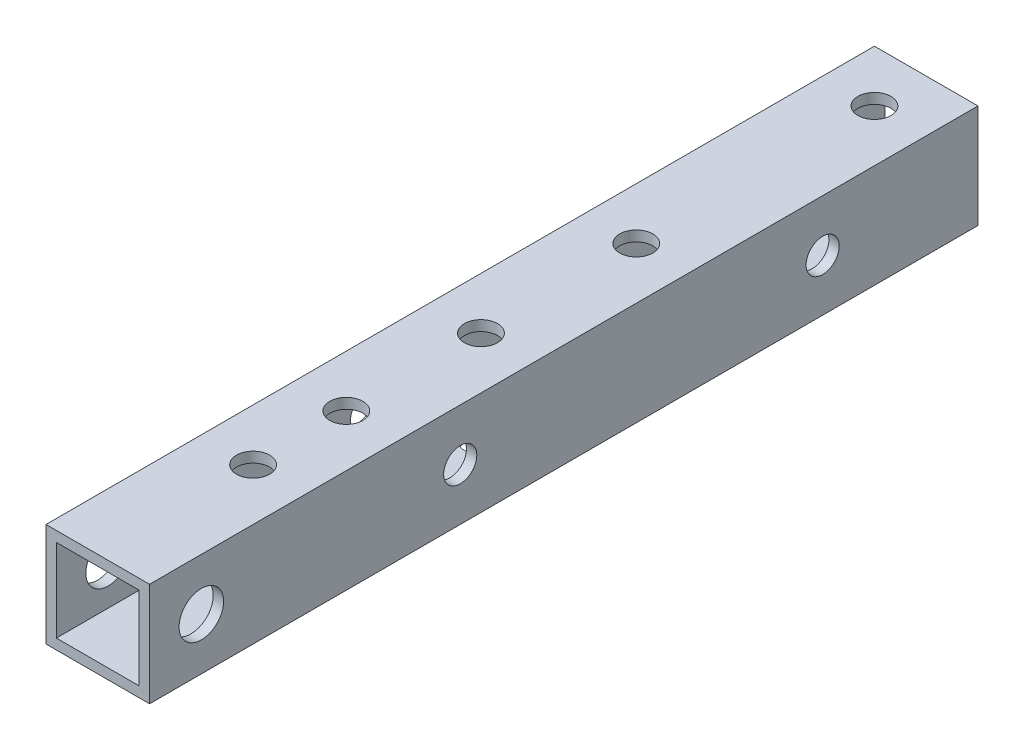
SolidWorks part; units mm, degrees
material "1060 合金"
ref_plane "正面" through (0, 0, 0) normal (0, 0, 1) x (1, 0, 0)
ref_plane "平面" through (0, 0, 0) normal (0, 1, 0) x (1, 0, 0)
ref_plane "右側面" through (0, 0, 0) normal (1, 0, 0) x (0, 0, -1)
sketch "ｽｹｯﾁ1" plane through (0, 0, 0) normal (0, 0, 1) x (1, 0, 0)
  line L1 (5, 5) -> (-5, 5)
  line L2 (5, 5) -> (5, -5)
  line L3 (5, -5) -> (-5, -5)
  line L4 (-5, 5) -> (-5, -5)
  line L5 (5, 5) -> (-5, -5) construction
  line L6 (5, -5) -> (-5, 5) construction
  point P0 (0, 0)
  dimension "D1" = 10
extrude "押し出し-薄板1" add sketch "ｽｹｯﾁ1" along normal blind 80 thin thin type one direction reverse wall 1
sketch "ｽｹｯﾁ2" plane through (0, 5, 0) normal (0, 1, 0) x (1, 0, 0)
  line L0 (0, 0) -> (0, -80) construction
  line L1 (5, 0) -> (-5, 0) construction
  line L2 (5, -80) -> (-5, -80) construction
  circle A0 centre (0, -5) radius 1.6
  dimension "D1" = 3.2
  dimension "D2" = 5
extrude "ｶｯﾄ - 押し出し1" cut sketch "ｽｹｯﾁ2" against normal through all
sketch "ｽｹｯﾁ3" plane through (5, 0, 0) normal (1, 0, 0) x (0, 0, -1)
  line L0 (0, 0) -> (-80, 0) construction
  line L1 (-80, -5) -> (-80, 5) construction
  line L2 (0, -5) -> (0, 5) construction
  circle A0 centre (-15, 0) radius 1.6
  dimension "D1" = 15
  dimension "D2" = 3.2
extrude "ｶｯﾄ - 押し出し2" cut sketch "ｽｹｯﾁ3" against normal through all
sketch "ｽｹｯﾁ4" plane through (0, -5, 0) normal (0, -1, 0) x (1, 0, 0)
  line L0 (0, 80) -> (0, 0) construction
  line L1 (-5, 80) -> (5, 80) construction
  line L2 (-5, 0) -> (5, 0) construction
  circle A0 centre (0, 65) radius 1.6
  circle A1 centre (0, 56) radius 1.6
  dimension "D1" = 9
  dimension "D2" = 15
  dimension "D3" = 3.2
extrude "ｶｯﾄ - 押し出し3" cut sketch "ｽｹｯﾁ4" against normal through all
sketch "ｽｹｯﾁ5" plane through (-5, 0, 0) normal (-1, 0, 0) x (0, 0, 1)
  line L0 (0, 0) -> (80, 0) construction
  line L1 (80, 5) -> (80, -5) construction
  circle A0 centre (50, 0) radius 1.6
  dimension "D1" = 3.2
  dimension "D2" = 30
extrude "ｶｯﾄ - 押し出し4" cut sketch "ｽｹｯﾁ5" against normal through all
sketch "ｽｹｯﾁ6" plane through (0, 5, 0) normal (0, 1, 0) x (1, 0, 0)
  line L0 (0, 0) -> (0, -80) construction
  line L1 (5, 0) -> (-5, 0) construction
  line L2 (5, -80) -> (-5, -80) construction
  circle A0 centre (0, -43) radius 1.6
  circle A1 centre (0, -28) radius 1.6
  dimension "D1" = 3.2
  dimension "D2" = 15
  dimension "D3" = 43
extrude "ｶｯﾄ - 押し出し5" cut sketch "ｽｹｯﾁ6" against normal through all
sketch "ｽｹｯﾁ7" plane through (5, 0, 0) normal (1, 0, 0) x (0, 0, -1)
  line L0 (-80, 0) -> (0, 0) construction
  line L1 (-80, -5) -> (-80, 5) construction
  circle A0 centre (-75, 0) radius 2.15
  dimension "D1" = 5
  dimension "D2" = 4.3
extrude "ｶｯﾄ - 押し出し6" cut sketch "ｽｹｯﾁ7" against normal through all
